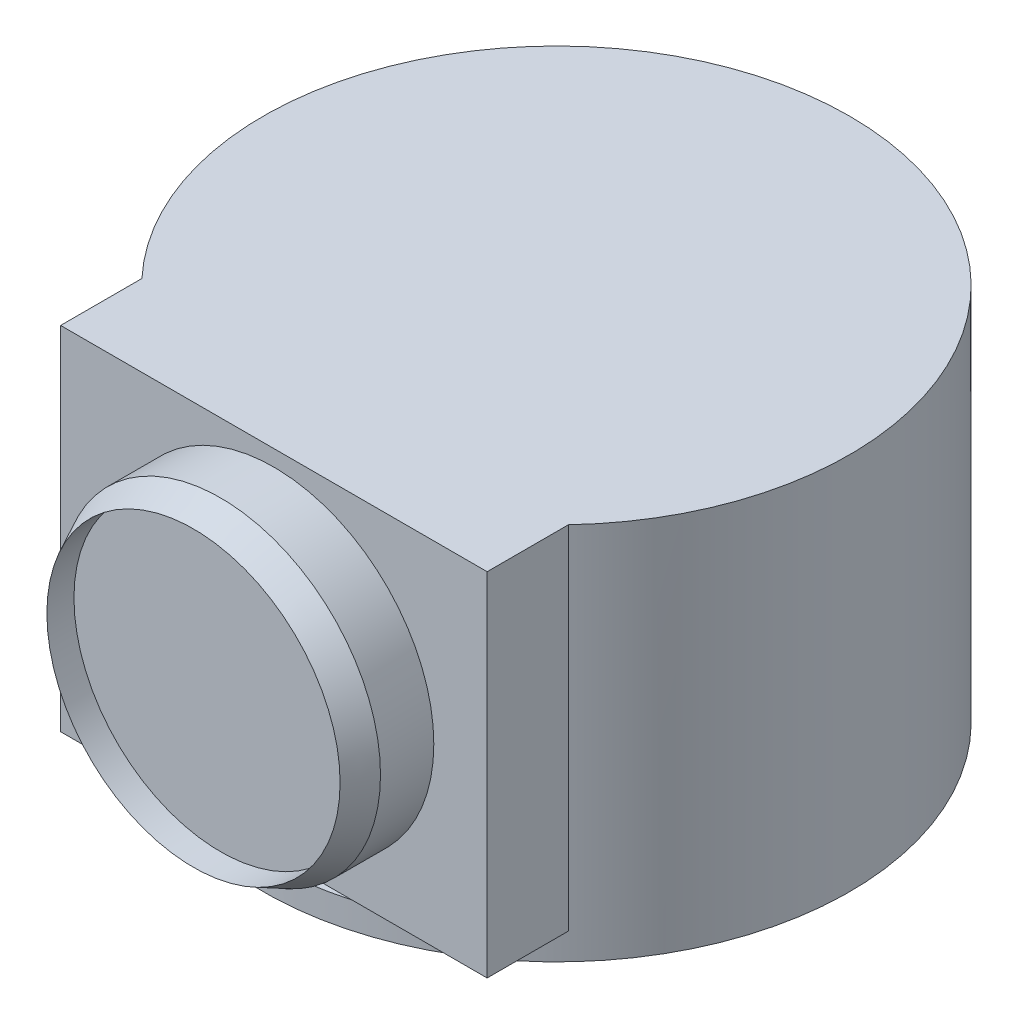
SolidWorks part; units mm, degrees
ref_plane "Front Plane" through (0, 0, 0) normal (0, 0, 1) x (1, 0, 0)
ref_plane "Top Plane" through (0, 0, 0) normal (0, 1, 0) x (1, 0, 0)
ref_plane "Right Plane" through (0, 0, 0) normal (1, 0, 0) x (0, 0, -1)
sketch "Sketch1" plane through (0, 0, 0) normal (0, 1, 0) x (1, 0, 0)
  circle A0 centre (0, 0) radius 55
extrude "Boss-Extrude1" add sketch "Sketch1" along normal blind 66
sketch "Sketch2" plane through (0, 0, 0) normal (0, 0, 1) x (1, 0, 0)
  line L0 (0, 0) -> (-80, 0) construction
  line L1 (-55, 0) -> (55, 0) construction
  line L3 (-40, 0) -> (-40, 66)
  line L7 (0, 0) -> (-40, 0)
  line L8 (55, 66) -> (-55, 66) construction
  line L9 (-40, 66) -> (40, 66)
  line L10 (40, 66) -> (40, 0)
  line L11 (40, 0) -> (-40, 0)
  line L12 (0, 0) -> (40, 0)
extrude "Boss-Extrude3" add sketch "Sketch2" along normal blind 63 contours L11 L10 L9 L3 L7
sketch "Sketch3" plane through (0, 0, 63) normal (0, 0, 1) x (1, 0, 0)
  line L0 (0, 0) -> (0, 33) construction
  line L3 (40, 0) -> (-40, 0) construction
  circle A1 centre (0, 33) radius 30
sketch "Sketch4" plane through (0, 0, 0) normal (1, 0, 0) x (0, 0, -1)
  line L0 (-63, 33) -> (-63, 5.5)
  line L1 (-63, 63) -> (-63, 3) construction
  line L2 (-63, 0) -> (-63, 33) construction
  line L3 (-63, 5.5) -> (-68.077, 5.5)
  line L4 (-63, 5.5) -> (-63, 3)
  line L5 (-63, 3) -> (-68.077, 5.5)
  line L6 (-63, 33) -> (-70.1732, 33) construction
revolve "Revolve1" add sketch "Sketch4" angle 360 about L6
sketch "Sketch5" plane through (0, 0, 63) normal (0, 0, 1) x (1, 0, 0)
  circle A0 centre (0, 33) radius 30
  circle A1 centre (0, 33) radius 56.243
extrude "Cut-Extrude2" cut sketch "Sketch5" against normal blind 10
sketch "Sketch6" plane through (0, 0, 0) normal (0, -1, 0) x (-1, 0, 0)
  circle A0 centre (0, 0) radius 55
extrude "Boss-Extrude4" add sketch "Sketch6" along normal blind 5
